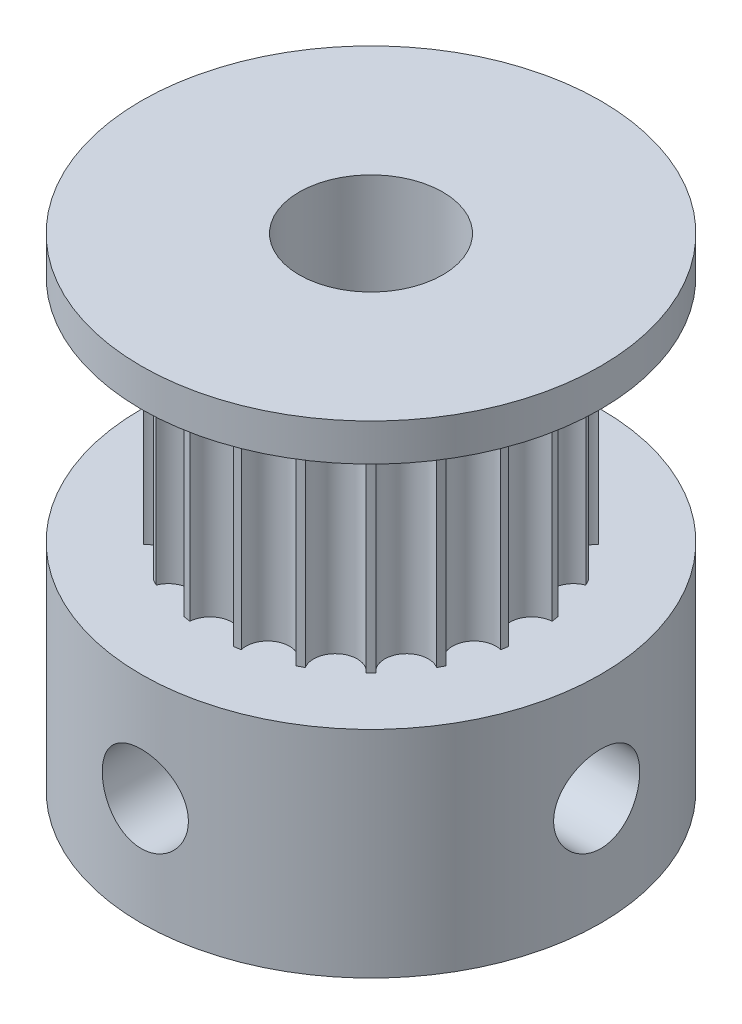
SolidWorks part; units mm, degrees
material "1060 Alloy"
ref_plane "Front Plane" through (0, 0, 0) normal (0, 0, 1) x (1, 0, 0)
ref_plane "Top Plane" through (0, 0, 0) normal (0, 1, 0) x (1, 0, 0)
ref_plane "Right Plane" through (0, 0, 0) normal (1, 0, 0) x (0, 0, -1)
sketch "Sketch1" plane through (0, 0, 0) normal (0, 1, 0) x (1, 0, 0)
  arc A0 (-2.4357, 5.0426) -> (-2.6478, 4.9345) centre (0, 0) ccw
  arc A1 (-0.7582, 5.5484) -> (0.7582, 5.5484) centre (0, 5.6) ccw
  arc A2 (0.9934, 5.5112) -> (2.4357, 5.0426) centre (1.7305, 5.3259) ccw
  arc A3 (2.6478, 4.9345) -> (3.8747, 4.0431) centre (3.2916, 4.5305) ccw
  arc A4 (4.0431, 3.8747) -> (4.9345, 2.6478) centre (4.5305, 3.2916) ccw
  arc A5 (5.0426, 2.4357) -> (5.5112, 0.9934) centre (5.3259, 1.7305) ccw
  arc A6 (5.5484, 0.7582) -> (5.5484, -0.7582) centre (5.6, 0) ccw
  arc A7 (5.5112, -0.9934) -> (5.0426, -2.4357) centre (5.3259, -1.7305) ccw
  arc A8 (4.9345, -2.6478) -> (4.0431, -3.8747) centre (4.5305, -3.2916) ccw
  arc A9 (3.8747, -4.0431) -> (2.6478, -4.9345) centre (3.2916, -4.5305) ccw
  arc A10 (2.4357, -5.0426) -> (0.9934, -5.5112) centre (1.7305, -5.3259) ccw
  arc A11 (0.7582, -5.5484) -> (-0.7582, -5.5484) centre (0, -5.6) ccw
  arc A12 (-0.9934, -5.5112) -> (-2.4357, -5.0426) centre (-1.7305, -5.3259) ccw
  arc A13 (-2.6478, -4.9345) -> (-3.8747, -4.0431) centre (-3.2916, -4.5305) ccw
  arc A14 (-4.0431, -3.8747) -> (-4.9345, -2.6478) centre (-4.5305, -3.2916) ccw
  arc A15 (-5.0426, -2.4357) -> (-5.5112, -0.9934) centre (-5.3259, -1.7305) ccw
  arc A16 (-5.5484, -0.7582) -> (-5.5484, 0.7582) centre (-5.6, 0) ccw
  arc A17 (-5.5112, 0.9934) -> (-5.0426, 2.4357) centre (-5.3259, 1.7305) ccw
  arc A18 (-4.9345, 2.6478) -> (-4.0431, 3.8747) centre (-4.5305, 3.2916) ccw
  arc A19 (-3.8747, 4.0431) -> (-2.6478, 4.9345) centre (-3.2916, 4.5305) ccw
  arc A20 (-2.4357, 5.0426) -> (-0.9934, 5.5112) centre (-1.7305, 5.3259) ccw
  arc A21 (-0.7582, 5.5484) -> (-0.9934, 5.5112) centre (0, 0) ccw
  arc A22 (0.9934, 5.5112) -> (0.7582, 5.5484) centre (0, 0) ccw
  arc A23 (2.6478, 4.9345) -> (2.4357, 5.0426) centre (0, 0) ccw
  arc A24 (4.0431, 3.8747) -> (3.8747, 4.0431) centre (0, 0) ccw
  arc A25 (5.0426, 2.4357) -> (4.9345, 2.6478) centre (0, 0) ccw
  arc A26 (5.5484, 0.7582) -> (5.5112, 0.9934) centre (0, 0) ccw
  arc A27 (5.5112, -0.9934) -> (5.5484, -0.7582) centre (0, 0) ccw
  arc A28 (4.9345, -2.6478) -> (5.0426, -2.4357) centre (0, 0) ccw
  arc A29 (3.8747, -4.0431) -> (4.0431, -3.8747) centre (0, 0) ccw
  arc A30 (2.4357, -5.0426) -> (2.6478, -4.9345) centre (0, 0) ccw
  arc A31 (0.7582, -5.5484) -> (0.9934, -5.5112) centre (0, 0) ccw
  arc A32 (-0.9934, -5.5112) -> (-0.7582, -5.5484) centre (0, 0) ccw
  arc A33 (-2.6478, -4.9345) -> (-2.4357, -5.0426) centre (0, 0) ccw
  arc A34 (-4.0431, -3.8747) -> (-3.8747, -4.0431) centre (0, 0) ccw
  arc A35 (-5.0426, -2.4357) -> (-4.9345, -2.6478) centre (0, 0) ccw
  arc A36 (-5.5484, -0.7582) -> (-5.5112, -0.9934) centre (0, 0) ccw
  arc A37 (-5.5112, 0.9934) -> (-5.5484, 0.7582) centre (0, 0) ccw
  arc A38 (-4.9345, 2.6478) -> (-5.0426, 2.4357) centre (0, 0) ccw
  arc A39 (-3.8747, 4.0431) -> (-4.0431, 3.8747) centre (0, 0) ccw
  point P46 (0, 0)
  dimension "D1" = 11.2
  dimension "D2" = 1.52
  dimension "D3" = 20
extrude "Boss-Extrude1" add sketch "Sketch1" along normal blind 8
sketch "Sketch2" plane through (0, 8, 0) normal (0, 1, 0) x (1, 0, 0)
  circle A0 centre (0, 0) radius 8
  dimension "D1" = 16
extrude "Boss-Extrude2" add sketch "Sketch2" along normal blind 1.3
sketch "Sketch3" plane through (0, 0, 0) normal (0, -1, 0) x (1, 0, 0)
  circle A0 centre (0, 0) radius 8
extrude "Boss-Extrude3" add sketch "Sketch3" along normal blind 7.5
sketch "Sketch4" plane through (0, -7.5, 0) normal (0, -1, 0) x (1, 0, 0)
  circle A0 centre (0, 0) radius 2.5
  dimension "D1" = 5
extrude "Cut-Extrude1" cut sketch "Sketch4" against normal blind 18.5
sketch "Sketch5" plane through (0, 0, 0) normal (1, 0, 0) x (0, 0, -1)
  line L0 (8, 0) -> (-8, 0) construction
  circle A0 centre (0, -3.75) radius 1.5
  dimension "D1" = 3
  dimension "D2" = 3.75
extrude "Cut-Extrude2" cut sketch "Sketch5" along normal blind 10.5
sketch "Sketch6" plane through (0, 0, 0) normal (0, 0, 1) x (1, 0, 0)
  line L0 (-8, -7.5) -> (8, -7.5) construction
  circle A0 centre (0, -3.75) radius 1.5
  dimension "D1" = 3
  dimension "D2" = 3.75
extrude "Cut-Extrude3" cut sketch "Sketch6" along normal blind 16.5
